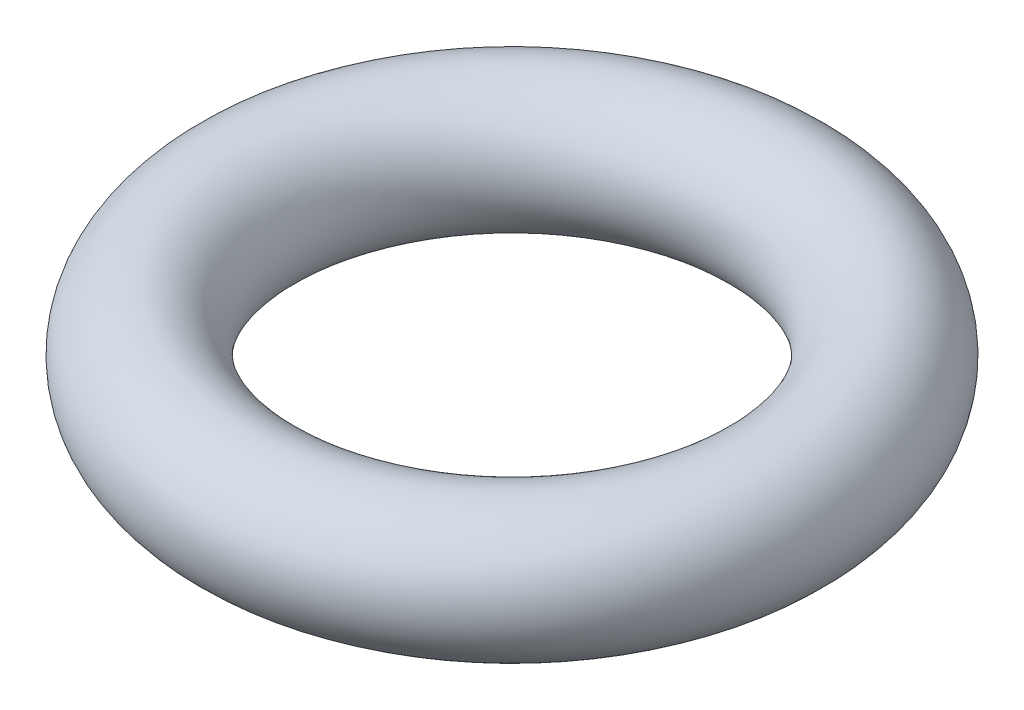
SolidWorks part; units mm, degrees
ref_plane "Front" through (0, 0, 0) normal (0, 0, 1) x (1, 0, 0)
ref_plane "Top" through (0, 0, 0) normal (0, 1, 0) x (1, 0, 0)
ref_plane "Right" through (0, 0, 0) normal (1, 0, 0) x (0, 0, -1)
sketch "Sketch1" plane through (0, 0, 0) normal (0, 0, 1) x (1, 0, 0)
  line L3 (0, 0) -> (0, 25.4) construction
  circle A0 centre (50.8, 12.7) radius 12.7
  point P6 (0, 12.7)
  dimension "D1" = 25.4
  dimension "D2" = 25.4
  dimension "D3" = 50.8
revolve "Revolve1" add sketch "Sketch1" angle 360 about L3
